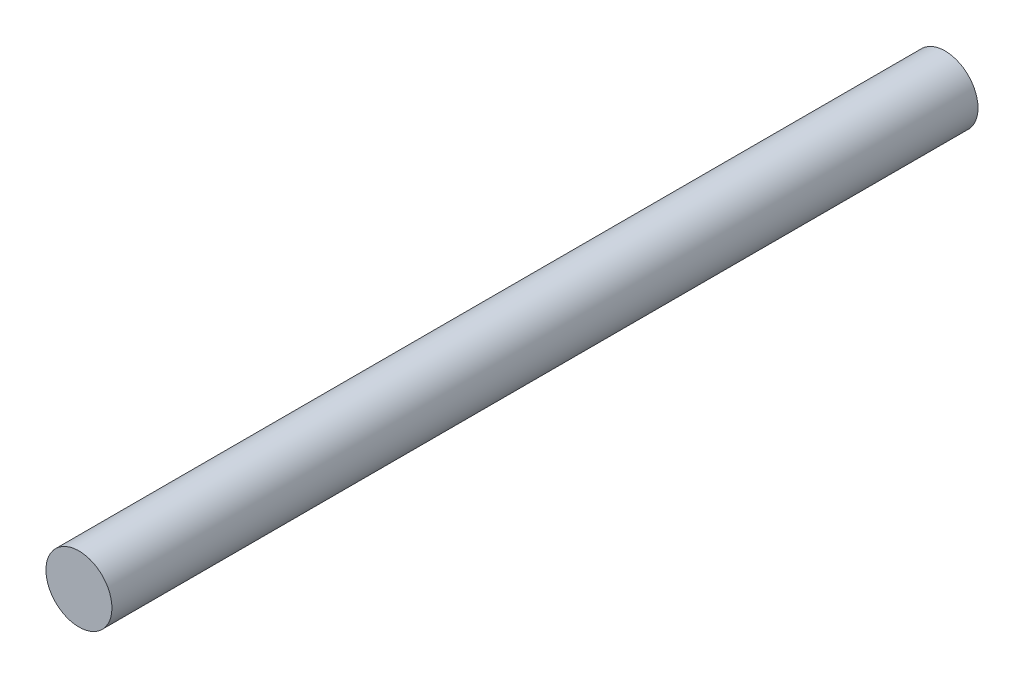
SolidWorks part; units mm, degrees
ref_plane "Front Plane" through (0, 0, 0) normal (0, 0, 1) x (1, 0, 0)
ref_plane "Top Plane" through (0, 0, 0) normal (0, 1, 0) x (1, 0, 0)
ref_plane "Right Plane" through (0, 0, 0) normal (1, 0, 0) x (0, 0, -1)
sketch "Sketch1" plane through (0, 0, 0) normal (0, 0, 1) x (1, 0, 0)
  circle A0 centre (0, 0) radius 4
  dimension "D1" = 8
extrude "Boss-Extrude1" add sketch "Sketch1" along normal blind 105
